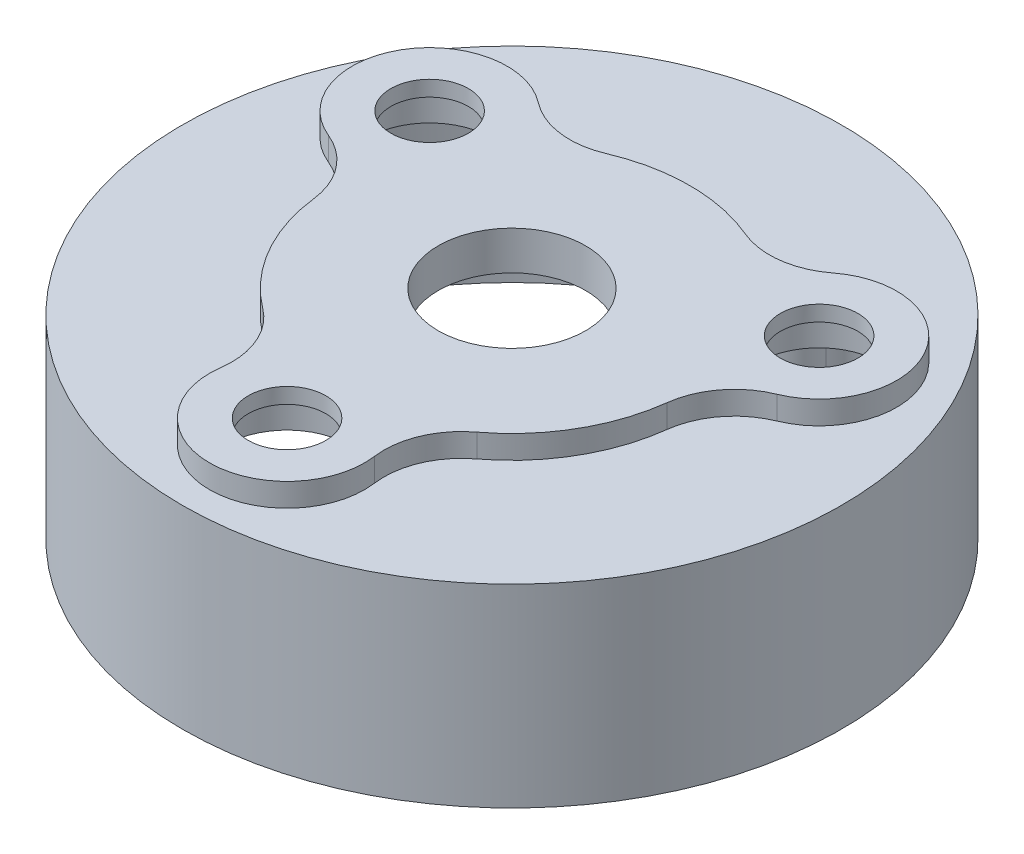
SolidWorks part; units mm, degrees
ref_plane "Front Plane" through (0, 0, 0) normal (0, 0, 1) x (1, 0, 0)
ref_plane "Top Plane" through (0, 0, 0) normal (0, 1, 0) x (1, 0, 0)
ref_plane "Right Plane" through (0, 0, 0) normal (1, 0, 0) x (0, 0, -1)
sketch "Sketch1" plane through (0, 0, 0) normal (0, 1, 0) x (1, 0, 0)
  circle A0 centre (0, 0) radius 42.5
  dimension "D1" = 85
extrude "Boss-Extrude1" add sketch "Sketch1" along normal blind 25
sketch "Sketch2" plane through (0, 25, 0) normal (0, 1, 0) x (1, 0, 0)
  circle A0 centre (0, 0) radius 22.945
  dimension "D1" = 45.89
extrude "Boss-Extrude2" add sketch "Sketch2" along normal blind 3
sketch "Sketch3" plane through (0, 28, 0) normal (0, 1, 0) x (1, 0, 0)
  circle A0 centre (0, 0) radius 9.5
  dimension "D1" = 19
extrude "Cut-Extrude1" cut sketch "Sketch3" against normal blind 99
sketch "Sketch4" plane through (0, 0, 0) normal (0, -1, 0) x (1, 0, 0)
  circle A0 centre (0, 0) radius 40.5
  circle A1 centre (0, 0) radius 42.5 construction
  dimension "D1" = 2
extrude "Cut-Extrude2" cut sketch "Sketch4" against normal offset from surface (23 mm away) 2 up to face at (0, 25, 22.945)
sketch "Sketch6" plane through (0, 23, 0) normal (0, -1, 0) x (-1, 0, 0)
  line L0 (0, -19) -> (0, -29) construction
  circle A1 centre (25.1147, 14.5) radius 10
  circle A2 centre (-25.1147, 14.5) radius 10
  circle A3 centre (0, -29) radius 10
extrude "Boss-Extrude5" add sketch "Sketch6" against normal blind 5 and the other way blind 2 contours A1 | A3 | A2
sketch "Sketch8" plane through (0, 23, 0) normal (0, -1, 0) x (1, 0, 0)
  circle A0 centre (0, 29) radius 8
  circle A1 centre (25.1147, -14.5) radius 8
  circle A2 centre (-25.1147, -14.5) radius 8
  dimension "D3" = 16
extrude "Cut-Extrude5" cut sketch "Sketch8" against normal blind 8 from offset 5
sketch "Sketch9" plane through (0, 28, 0) normal (0, 1, 0) x (1, 0, 0)
  circle A0 centre (-25.1147, 14.5) radius 5
  circle A1 centre (25.1147, 14.5) radius 5
  circle A2 centre (0, -29) radius 5
  dimension "D1" = 10
  dimension "D2" = 10
  dimension "D3" = 10
extrude "Cut-Extrude6" cut sketch "Sketch9" against normal blind 3
fillet "Fillet1" radius 10 6 edges at (-6.9943, 26.5, 21.853) (6.9943, 26.5, 21.853) (22.4224, 26.5, -4.8693) (15.4281, 26.5, -16.9837) (-15.4281, 26.5, -16.9837) (-22.4224, 26.5, -4.8693)
sketch "Sketch5" plane through (0, 23, 0) normal (0, -1, 0) x (1, 0, 0)
  circle A0 centre (0, 0) radius 20
  circle A1 centre (0, 0) radius 12.5
  dimension "D1" = 40
  dimension "D2" = 25
extrude "Cut-Extrude3" cut sketch "Sketch5" against normal blind 3 and the other way through all
sketch "Sketch12" plane through (0, 23, 0) normal (0, -1, 0) x (1, 0, 0)
  line L0 (0, 0) -> (0, -40.5) construction
  circle A0 centre (0, 0) radius 40.5 construction
  circle A1 centre (0, -35.5) radius 2
  circle A2 centre (0, -35.5) radius 6
  circle A3 centre (-30.7439, 17.75) radius 2
  circle A4 centre (-30.7439, 17.75) radius 6
  circle A5 centre (30.7439, 17.75) radius 2
  circle A6 centre (30.7439, 17.75) radius 6
  point P18 (0, 0)
  dimension "D1" = 4
  dimension "D3" = 12
  dimension "D2" = 5
  dimension "D4" = 3
extrude "Boss-Extrude6" add sketch "Sketch12" along normal up to surface (23 mm away) up to face at (0, 0, -40.5)
fillet "Fillet2" radius 5 6 edges at (3.5391, 11.5, -40.3451) (-3.5391, 11.5, -40.3451) (33.1703, 11.5, 23.2375) (36.7094, 11.5, 17.1076) (-36.7094, 11.5, 17.1076) (-33.1703, 11.5, 23.2375)
